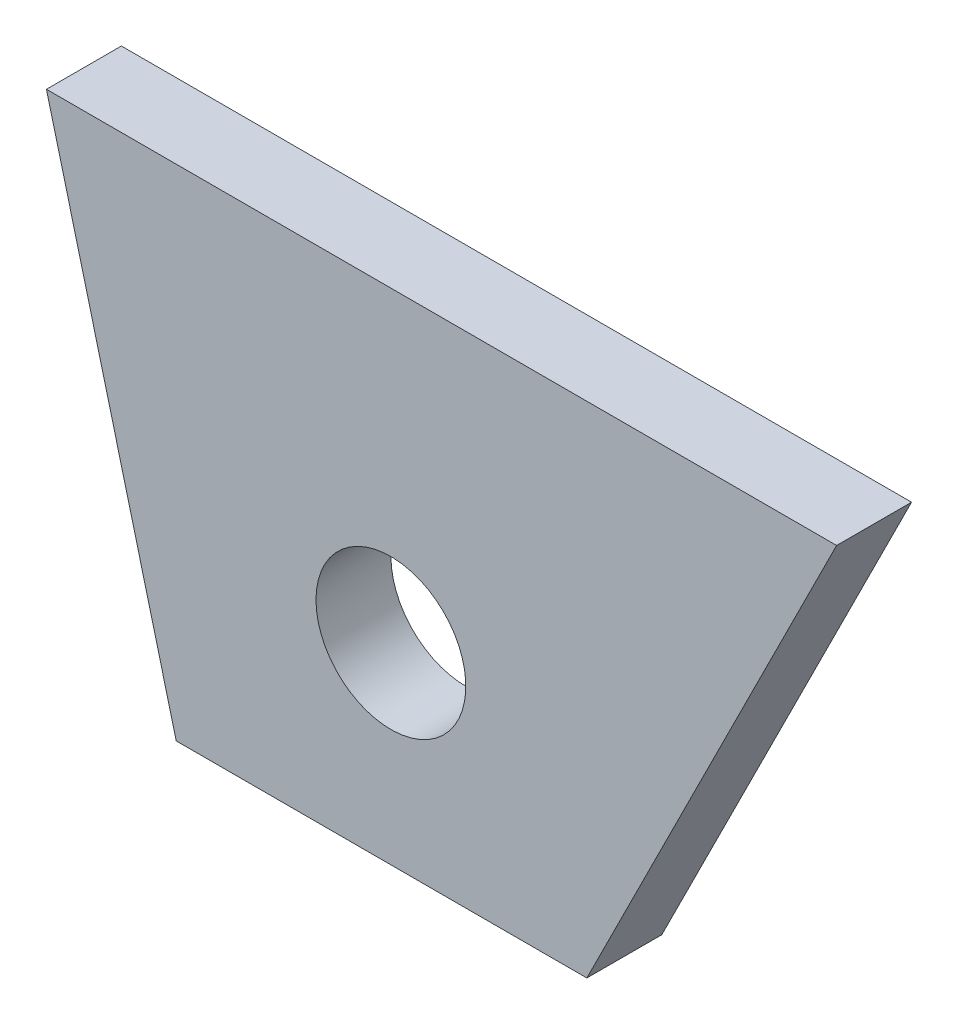
SolidWorks part; units mm, degrees
ref_plane "Front Plane" through (0, 0, 0) normal (0, 0, 1) x (1, 0, 0)
ref_plane "Top Plane" through (0, 0, 0) normal (0, 1, 0) x (1, 0, 0)
ref_plane "Right Plane" through (0, 0, 0) normal (1, 0, 0) x (0, 0, -1)
sketch "Sketch2" plane through (0, 0, 0) normal (0, 0, 1) x (1, 0, 0)
  line L0 (0, 0) -> (803.656, 0)
  line L1 (0, 0) -> (131.991, -508)
  line L2 (131.991, -508) -> (549.6157, -508)
  line L3 (549.6157, -508) -> (803.656, 0)
  circle A0 centre (350.3342, -312.5848) radius 76.2
  dimension "D1" = 803.656
  dimension "D2" = 508
extrude "Boss-Extrude2" add sketch "Sketch2" along normal blind 76.2
